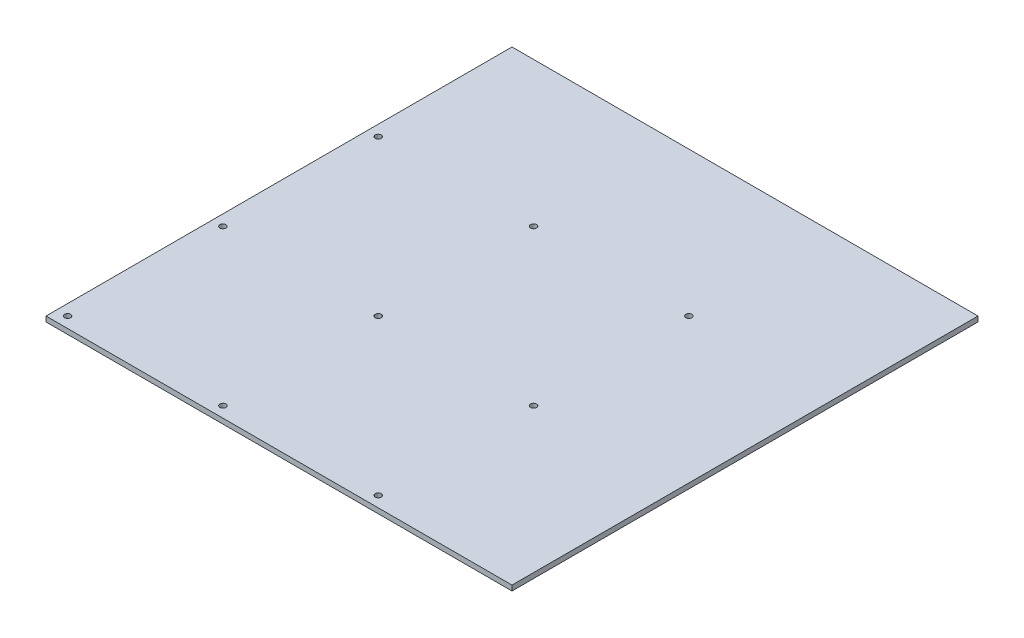
SolidWorks part; units mm, degrees
ref_plane "Front Plane" through (0, 0, 0) normal (0, 0, 1) x (1, 0, 0)
ref_plane "Top Plane" through (0, 0, 0) normal (0, 1, 0) x (1, 0, 0)
ref_plane "Right Plane" through (0, 0, 0) normal (1, 0, 0) x (0, 0, -1)
sketch "Sketch1" plane through (0, 0, 0) normal (0, 1, 0) x (1, 0, 0)
  line L0 (-257.5, -257.5) -> (-257.5, -270) construction
  line L5 (270, -270) -> (-270, -270)
  line L6 (270, -270) -> (270, 270)
  line L7 (270, 270) -> (-270, 270)
  line L8 (-270, -270) -> (-270, 270)
  line L9 (270, -270) -> (-270, 270) construction
  line L10 (270, 270) -> (-270, -270) construction
  line L11 (-257.5, -257.5) -> (-270, -257.5) construction
  circle A0 centre (-257.5, -257.5) radius 3.5
  circle A3 centre (-77.5, -257.5) radius 3.5
  circle A4 centre (102.5, -257.5) radius 3.5
  circle A5 centre (-77.5, -77.5) radius 3.5
  circle A6 centre (102.5, -77.5) radius 3.5
  circle A7 centre (-77.5, 102.5) radius 3.5
  circle A8 centre (102.5, 102.5) radius 3.5
  circle A9 centre (-257.5, -77.5) radius 3.5
  circle A10 centre (-257.5, 102.5) radius 3.5
  point P0 (0, 0)
  dimension "D3" = 7
  dimension "D1" = 540
  dimension "D2" = 540
  dimension "D4" = 12.5
  dimension "D5" = 12.5
  dimension "D6" = 3
  dimension "D7" = 3
extrude "Boss-Extrude1" add sketch "Sketch1" along normal blind 6
equation "\"hole\" = 7mm'UK=6, HK=7, JP=8?"
equation "\"D3@Sketch1\"=\"hole\""
